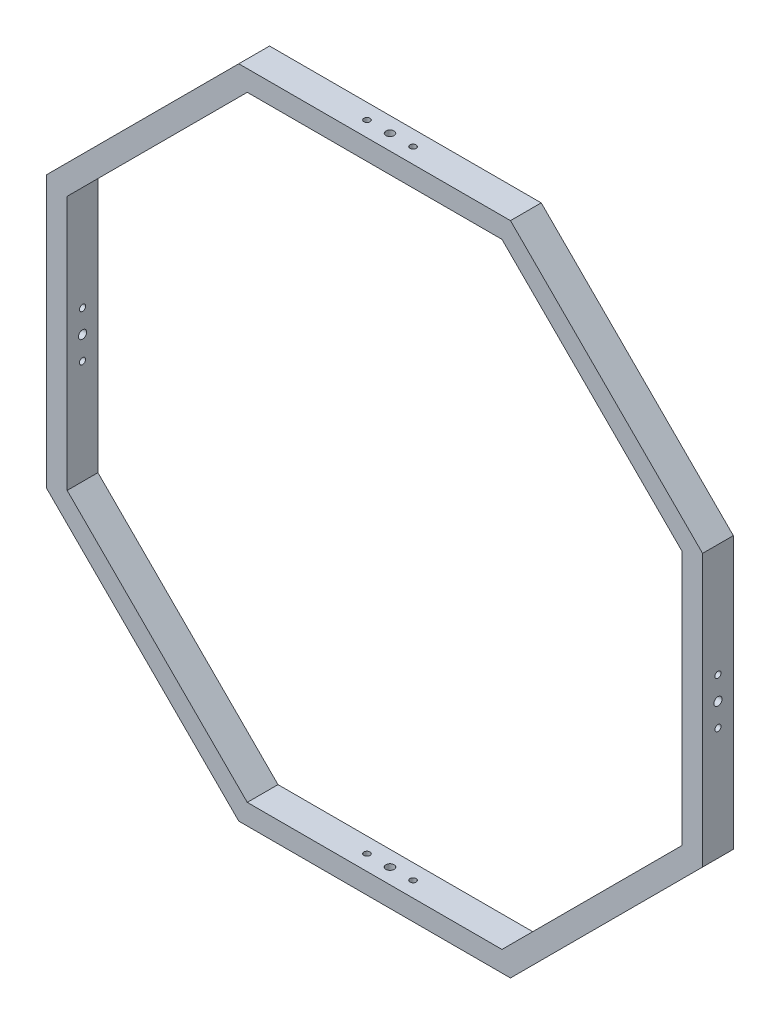
SolidWorks part; units mm, degrees
ref_plane "Front Plane" through (0, 0, 0) normal (0, 0, 1) x (1, 0, 0)
ref_plane "Top Plane" through (0, 0, 0) normal (0, 1, 0) x (1, 0, 0)
ref_plane "Right Plane" through (0, 0, 0) normal (1, 0, 0) x (0, 0, -1)
sketch "Sketch1" plane through (0, 0, 0) normal (0, 0, 1) x (1, 0, 0)
  line L0 (265.0967, 640) -> (-265.0967, 640)
  line L13 (600, -248.5281) -> (600, 248.5281)
  line L14 (600, 248.5281) -> (248.5281, 600)
  line L15 (248.5281, 600) -> (-248.5281, 600)
  line L16 (-248.5281, 600) -> (-600, 248.5281)
  line L17 (-600, 248.5281) -> (-600, -248.5281)
  line L18 (-600, -248.5281) -> (-248.5281, -600)
  line L19 (-248.5281, -600) -> (248.5281, -600)
  line L20 (248.5281, -600) -> (600, -248.5281)
  line L21 (-265.0967, 640) -> (-640, 265.0967)
  line L22 (-640, 265.0967) -> (-640, -265.0967)
  line L23 (-640, -265.0967) -> (-265.0967, -640)
  line L24 (-265.0967, -640) -> (265.0967, -640)
  line L25 (265.0967, -640) -> (640, -265.0967)
  line L26 (640, -265.0967) -> (640, 265.0967)
  line L27 (640, 265.0967) -> (265.0967, 640)
  circle A0 centre (0, 0) radius 600 construction
  point P85 (0, 0)
  dimension "D1" = 1200
  dimension "D3" = 530.1934
  dimension "D4" = 497.0563
  dimension "D2" = 40
extrude "Boss-Extrude1" add sketch "Sketch1" along normal blind 60
sketch "Sketch2" plane through (640, 0, 0) normal (1, 0, 0) x (0, 0, -1)
  line L0 (-30, 265.0967) -> (-30, -265.0967) construction
  line L1 (-60, 265.0967) -> (0, 265.0967) construction
  line L2 (-60, -265.0967) -> (0, -265.0967) construction
  line L3 (-60, 0) -> (0, 0) construction
  line L4 (-60, -265.0967) -> (-60, 265.0967) construction
  line L5 (0, -265.0967) -> (0, 265.0967) construction
  circle A0 centre (-30, 0) radius 8
  circle A1 centre (-30, 45) radius 6
  circle A2 centre (-30, -45) radius 6
  dimension "D1" = 16
  dimension "D2" = 12
  dimension "D3" = 45
  dimension "D4" = 12
  dimension "D5" = 45
extrude "Cut-Extrude1" cut sketch "Sketch2" against normal blind 1899
sketch "Sketch3" plane through (0, -640, 0) normal (0, -1, 0) x (1, 0, 0)
  line L0 (-265.0967, 30) -> (265.0967, 30) construction
  line L1 (-265.0967, 60) -> (-265.0967, 0) construction
  line L2 (265.0967, 60) -> (265.0967, 0) construction
  line L3 (0, 0) -> (0, 60) construction
  line L4 (-265.0967, 0) -> (265.0967, 0) construction
  line L5 (-265.0967, 60) -> (265.0967, 60) construction
  circle A0 centre (0, 30) radius 8
  circle A1 centre (-45, 30) radius 6
  circle A2 centre (45, 30) radius 6
  dimension "D1" = 16
  dimension "D2" = 12
  dimension "D3" = 12
  dimension "D4" = 45
  dimension "D5" = 45
extrude "Cut-Extrude2" cut sketch "Sketch3" against normal blind 1899
